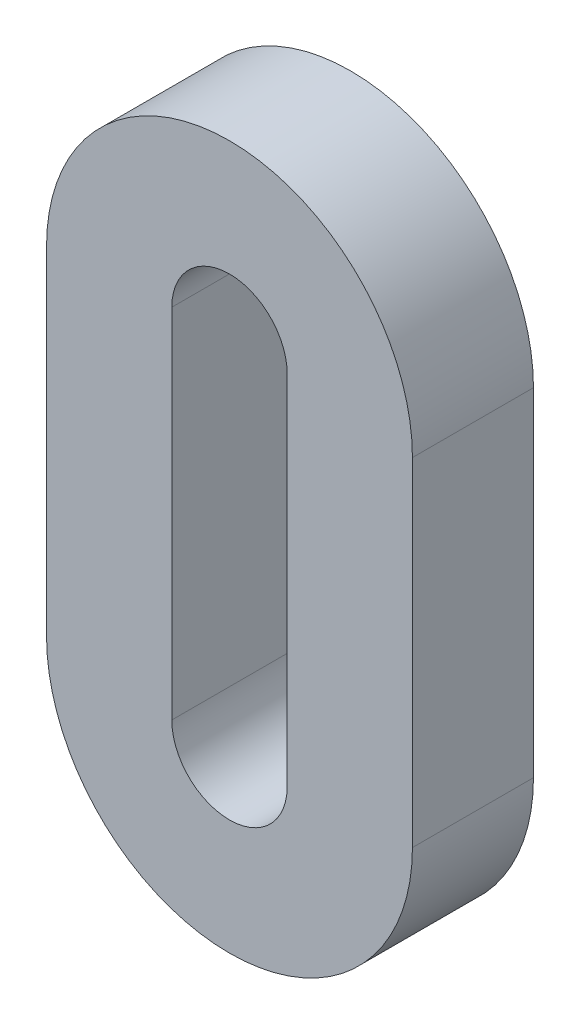
SolidWorks part; units mm, degrees
ref_plane "Front Plane" through (0, 0, 0) normal (0, 0, 1) x (1, 0, 0)
ref_plane "Top Plane" through (0, 0, 0) normal (0, 1, 0) x (1, 0, 0)
ref_plane "Right Plane" through (0, 0, 0) normal (1, 0, 0) x (0, 0, -1)
sketch "Sketch1" plane through (0, 0, 0) normal (0, 0, 1) x (1, 0, 0)
  line L0 (-18.0028, 6) -> (-18.0028, -6) construction
  line L1 (-11.5028, 6) -> (-11.5028, -6)
  line L2 (-24.5028, 6) -> (-24.5028, -6)
  line L13 (-18.0028, 6.35) -> (-18.0028, -6.35) construction
  line L20 (-15.9528, 6.35) -> (-15.9528, -6.35)
  line L21 (-20.0528, 6.35) -> (-20.0528, -6.35)
  arc A0 (-11.5028, 6) -> (-24.5028, 6) centre (-18.0028, 6) ccw
  arc A1 (-24.5028, -6) -> (-11.5028, -6) centre (-18.0028, -6) ccw
  arc A8 (-15.9528, 6.35) -> (-20.0528, 6.35) centre (-18.0028, 6.35) ccw
  arc A9 (-20.0528, -6.35) -> (-15.9528, -6.35) centre (-18.0028, -6.35) ccw
  point P3 (-18.0028, 0)
  point P38 (-18.0028, 0)
  point P67 (0, 0)
  dimension "D1" = 13
  dimension "D2" = 12
  dimension "D11" = 4.1
  dimension "D12" = 12.7
extrude "Boss-Extrude1" add sketch "Sketch1" along normal blind 4.3
